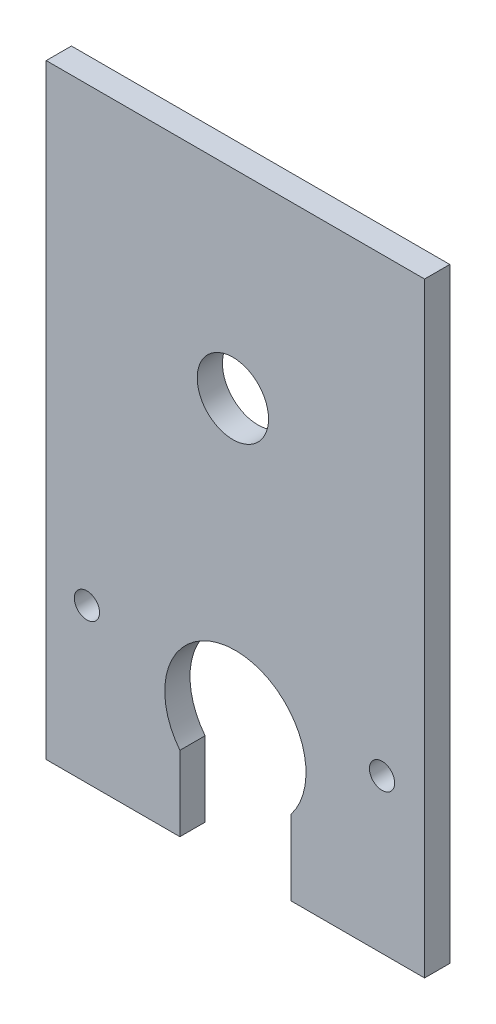
SolidWorks part; units mm, degrees
material "PW100:Mi:0:7:C1:0:1:2:Re:26:"
ref_plane "Plan1" through (0, 0, 0) normal (0, 0, 1) x (1, 0, 0)
ref_plane "Plan2" through (0, 0, 0) normal (0, 1, 0) x (1, 0, 0)
ref_plane "Plan3" through (0, 0, 0) normal (1, 0, 0) x (0, 0, -1)
sketch "Esquisse1" plane through (0, 0, 0) normal (0, 0, 1) x (1, 0, 0)
  line L1 (0, 0) -> (150, 0)
  line L2 (0, 0) -> (0, 240)
  line L3 (0, 240) -> (150, 240)
  line L4 (150, 0) -> (150, 240)
extrude "Base-Extrusion" add sketch "Esquisse1" along normal blind 10
sketch "Esquisse2" plane through (0, 0, 10) normal (0, 0, 1) x (1, 0, 0)
  line L0 (0, 0) -> (150, 0) construction
  line L1 (53, 0) -> (97, 0)
  line L2 (53, 0) -> (53, 29.6795)
  line L4 (97, 0) -> (97, 29.6795)
  arc A0 (97, 29.6795) -> (53, 29.6795) centre (75, 47) ccw
  dimension "D1" = 47
extrude "Enlèv. mat.-Extru.1" cut sketch "Esquisse2" against normal blind 10
sketch "Esquisse3" plane through (0, 0, 10) normal (0, 0, 1) x (1, 0, 0)
  line L0 (97, 0) -> (150, 0) construction
  circle A0 centre (74, 161) radius 14.1421
  dimension "D1" = 161
extrude "Enlèv. mat.-Extru.2" cut sketch "Esquisse3" against normal blind 10
sketch "Esquisse4" plane through (0, 0, 0) normal (0, 0, -1) x (-1, 0, 0)
  line L2 (0, 0) -> (-53, 0) construction
  line L3 (-97, 0) -> (-150, 0) construction
  circle A2 centre (-16.1429, 61) radius 5
  circle A3 centre (-133.1429, 61) radius 5
  dimension "D1" = 61
  dimension "D2" = 61
extrude "Enlèv. mat.-Extru.3" cut sketch "Esquisse4" against normal through all
sketch "Esquisse5" plane through (0, 0, 10) normal (0, 0, 1) x (1, 0, 0)
  line L0 (74, 161) -> (74, 222.4323) construction
